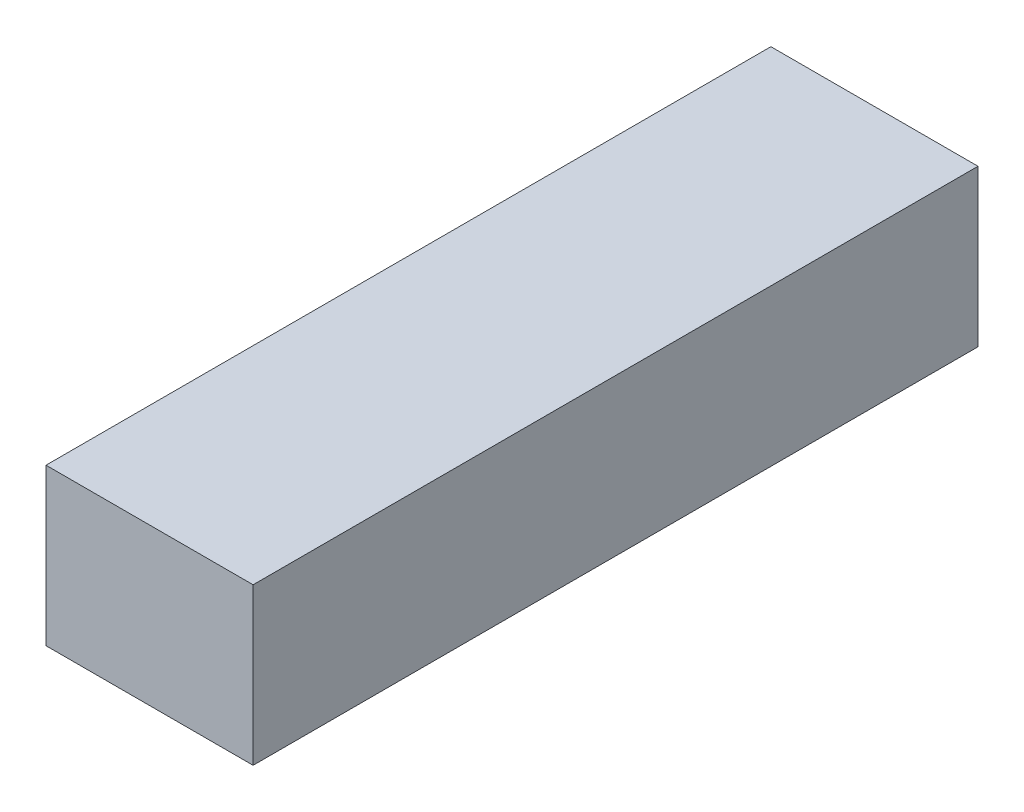
SolidWorks part; units mm, degrees
ref_plane "Front Plane" through (0, 0, 0) normal (0, 0, 1) x (1, 0, 0)
ref_plane "Top Plane" through (0, 0, 0) normal (0, 1, 0) x (1, 0, 0)
ref_plane "Right Plane" through (0, 0, 0) normal (1, 0, 0) x (0, 0, -1)
sketch "Sketch1" plane through (0, 0, 0) normal (0, 1, 0) x (1, 0, 0)
  line L0 (0, 0) -> (25.4, 0)
  line L1 (0, 0) -> (0, 88.9)
  line L2 (0, 88.9) -> (25.4, 88.9)
  line L3 (25.4, 88.9) -> (25.4, 0)
  dimension "D1" = 25.4
  dimension "D2" = 88.9
extrude "Boss-Extrude1" add sketch "Sketch1" along normal blind 19.177
